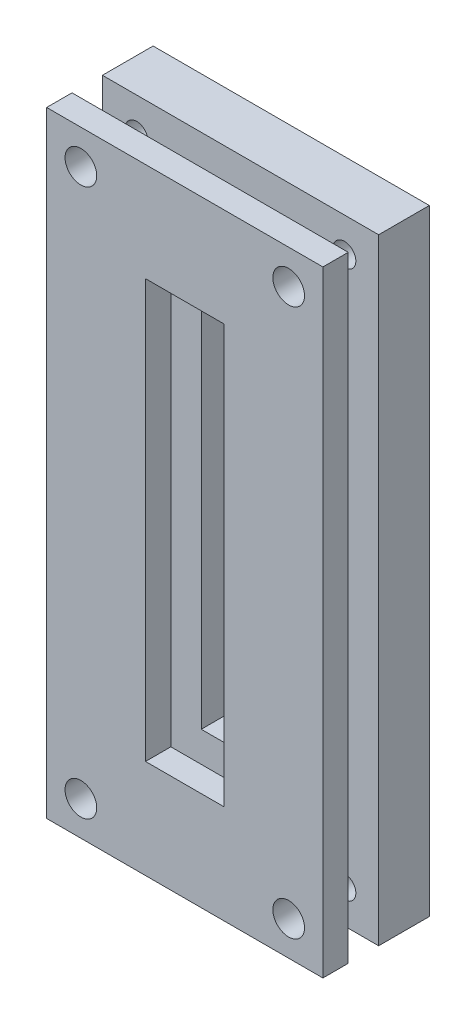
SolidWorks part; units mm, degrees
ref_plane "Front Plane" through (0, 0, 0) normal (0, 0, 1) x (1, 0, 0)
ref_plane "Top Plane" through (0, 0, 0) normal (0, 1, 0) x (1, 0, 0)
ref_plane "Right Plane" through (0, 0, 0) normal (1, 0, 0) x (0, 0, -1)
sketch "Sketch1" plane through (0, 0, 0) normal (0, 0, 1) x (1, 0, 0)
  line L1 (-3.1, 16.5) -> (3.1, 16.5)
  line L2 (-3.1, 16.5) -> (-3.1, -16.5)
  line L3 (-3.1, -16.5) -> (3.1, -16.5)
  line L4 (3.1, 16.5) -> (3.1, -16.5)
  line L5 (-3.1, 16.5) -> (3.1, -16.5) construction
  line L6 (-3.1, -16.5) -> (3.1, 16.5) construction
  point P0 (0, 0)
  point P5 (0, 0)
  dimension "D1" = 6.2
  dimension "D2" = 33
extrude "Boss-Extrude1" add sketch "Sketch1" along normal blind 4.5
shell "Shell1" thickness 2.4
sketch "Sketch2" plane through (0, 0, 4.5) normal (0, 0, 1) x (1, 0, 0)
  line L0 (10.9, -24.3) -> (10.9, 24.3)
  line L1 (10.9, 24.3) -> (-10.9, 24.3)
  line L2 (-10.9, 24.3) -> (-10.9, -24.3)
  line L3 (-10.9, -24.3) -> (10.9, -24.3)
  line L4 (5.5, -18.9) -> (5.5, 18.9)
  line L5 (5.5, 18.9) -> (-5.5, 18.9)
  line L6 (-5.5, 18.9) -> (-5.5, -18.9)
  line L7 (-5.5, -18.9) -> (5.5, -18.9)
  line L8 (5.5, -18.9) -> (5.5, 18.9)
  line L9 (5.5, 18.9) -> (-5.5, 18.9)
  line L10 (-5.5, 18.9) -> (-5.5, -18.9)
  line L11 (-5.5, -18.9) -> (5.5, -18.9)
  line L12 (-5.5, 18.9) -> (-10.9, 24.3) construction
  line L13 (5.5, 18.9) -> (10.9, 24.3) construction
  line L14 (-10.9, 0) -> (-24.408, 0) construction
  circle A0 centre (-8.2, 21.6) radius 0.9
  circle A1 centre (8.2, 21.6) radius 0.9
  circle A2 centre (8.2, -21.6) radius 0.9
  circle A3 centre (-8.2, -21.6) radius 0.9
  dimension "D3" = 1.8
  dimension "D1" = 0
  dimension "D2" = 5.4
extrude "Boss-Extrude2" add sketch "Sketch2" against normal blind 4
sketch "Sketch3" plane through (0, 0, 4.5) normal (0, 0, 1) x (1, 0, 0)
  line L4 (3.1, -16.5) -> (3.1, 16.5)
  line L5 (-3.1, -16.5) -> (3.1, -16.5)
  line L6 (-3.1, 16.5) -> (-3.1, -16.5)
  line L7 (3.1, 16.5) -> (-3.1, 16.5)
  line L8 (3.1, -16.5) -> (3.1, 16.5)
  line L9 (-3.1, -16.5) -> (3.1, -16.5)
  line L10 (-3.1, 16.5) -> (-3.1, -16.5)
  line L11 (3.1, 16.5) -> (-3.1, 16.5)
  line L12 (-10.9, -24.3) -> (10.9, -24.3)
  line L13 (10.9, -24.3) -> (10.9, 24.3)
  line L14 (10.9, 24.3) -> (-10.9, 24.3)
  line L15 (-10.9, 24.3) -> (-10.9, -24.3)
  line L16 (-10.9, -24.3) -> (10.9, -24.3)
  line L17 (10.9, -24.3) -> (10.9, 24.3)
  line L18 (10.9, 24.3) -> (-10.9, 24.3)
  line L19 (-10.9, 24.3) -> (-10.9, -24.3)
  circle A0 centre (-8.2, 21.6) radius 1.25
  circle A1 centre (-8.2, 21.6) radius 0.9
  circle A2 centre (-8.2, 21.6) radius 0.9 construction
  circle A3 centre (8.2, 21.6) radius 0.9
  circle A4 centre (8.2, 21.6) radius 0.9 construction
  circle A5 centre (8.2, -21.6) radius 0.9
  circle A6 centre (8.2, -21.6) radius 0.9 construction
  circle A7 centre (-8.2, -21.6) radius 0.9
  circle A8 centre (-8.2, -21.6) radius 0.9 construction
  circle A9 centre (8.2, 21.6) radius 1.25
  circle A10 centre (-8.2, -21.6) radius 1.25
  circle A11 centre (8.2, -21.6) radius 1.25
  dimension "D1" = 0
  dimension "D2" = 0
  dimension "D3" = 0
  dimension "D4" = 0
  dimension "D5" = 0
  dimension "D6" = 0
  dimension "D7" = 0.35
extrude "Boss-Extrude3" add sketch "Sketch3" along normal blind 2 from offset 2.4 separate body
